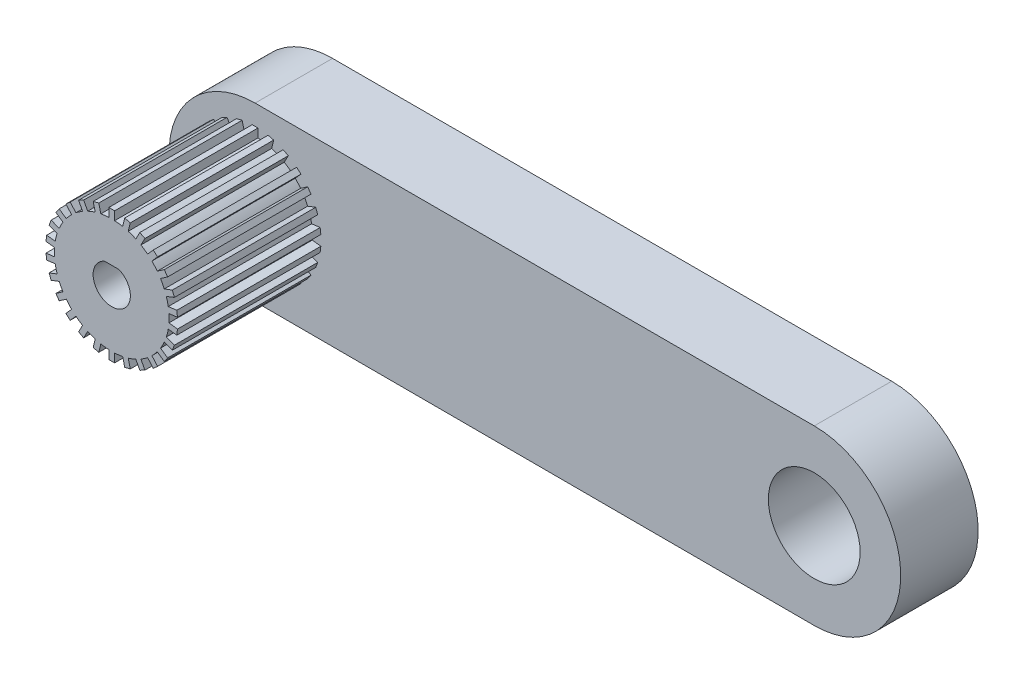
SolidWorks part; units mm, degrees
ref_plane "Front Plane" through (0, 0, 0) normal (0, 0, 1) x (1, 0, 0)
ref_plane "Top Plane" through (0, 0, 0) normal (0, 1, 0) x (1, 0, 0)
ref_plane "Right Plane" through (0, 0, 0) normal (1, 0, 0) x (0, 0, -1)
sketch "Sketch1" plane through (0, 0, 0) normal (0, 0, 1) x (1, 0, 0)
  line L1 (0, 15) -> (97.5002, 15)
  line L2 (0, -15) -> (97.4767, -15.1517)
  line L4 (32.5002, 7.4241) -> (97.5002, 7.4241)
  line L5 (32.5002, -7.5759) -> (97.5002, -7.5759)
  line L6 (32.5002, 7.4241) -> (32.5002, -7.5759)
  arc A0 (0, 15) -> (0, -15) centre (0, 0) ccw
  arc A1 (97.5002, -7.5759) -> (97.5002, 7.4241) centre (97.5002, -0.0759) ccw
  arc A2 (32.5002, 7.4241) -> (32.5002, -7.5759) centre (32.5002, -0.0759) ccw
  arc A3 (97.4767, -15.1517) -> (97.5002, 15) centre (97.5002, -0.0759) ccw
  dimension "D1" = 30
  dimension "D3" = 15
  dimension "D5" = 15
  dimension "D4" = 65
extrude "Boss-Extrude1" add sketch "Sketch1" along normal blind 15 contours L2 A3 L1 A0 A2 L4 A1 L5
sketch "Sketch2" plane through (0, 0, 15) normal (0, 0, 1) x (1, 0, 0)
  circle A0 centre (0, 0) radius 2.575
  circle A1 centre (0, 0) radius 10
  dimension "D1" = 5.15
  dimension "D2" = 20
extrude "Boss-Extrude2" add sketch "Sketch2" along normal blind 20
sketch "Sketch4" plane through (0, 0, 0) normal (0, 0, -1) x (-1, 0, 0)
  line L1 (120.8394, 33.9708) -> (-120.8394, 33.9708)
  line L2 (120.8394, 33.9708) -> (120.8394, -33.9708)
  line L3 (120.8394, -33.9708) -> (-120.8394, -33.9708)
  line L4 (-120.8394, 33.9708) -> (-120.8394, -33.9708)
  line L5 (120.8394, 33.9708) -> (-120.8394, -33.9708) construction
  line L6 (120.8394, -33.9708) -> (-120.8394, 33.9708) construction
  point P0 (0, 0)
extrude "Cut-Extrude2" cut sketch "Sketch4" against normal blind 1.5
sketch "Sketch5" plane through (0, 0, 35) normal (0, 0, 1) x (1, 0, 0)
  circle A0 centre (0, 0) radius 2.575
  circle A1 centre (0, 0) radius 10
extrude "Boss-Extrude3" add sketch "Sketch5" along normal blind 10
sketch "Sketch6" plane through (0, 0, 1.5) normal (0, 0, -1) x (-1, 0, 0)
  circle A0 centre (-97.5002, -0.0759) radius 8
  dimension "D1" = 16
extrude "Cut-Extrude3" cut sketch "Sketch6" against normal through all
sketch "Sketch7" plane through (0, 0, 1.5) normal (0, 0, -1) x (-1, 0, 0)
  line L0 (-94.7163, 7.4241) -> (-32.5002, 7.4241)
  line L1 (-94.7163, -7.5759) -> (-32.5002, -7.5759)
  circle A0 centre (-97.5002, -0.0759) radius 8
  circle A1 centre (-32.5002, -0.0759) radius 7.5
  line M1 (-32.5002, -7.5759) -> (-94.7163, -7.5759)
  line M3 (-94.7163, 7.4241) -> (-32.5002, 7.4241)
  arc M4 (-32.5002, 7.4241) -> (-32.5002, -7.5759) centre (-32.5002, -0.0759) cw
extrude "Boss-Extrude4" add sketch "Sketch7" against normal up to surface (13.5 mm away) contours A1 A0 M3 M1 | A1 M4 up to face at (64.4292, -0.0759, 15)
sketch "Sketch9" plane through (0, 0, 45) normal (0, 0, 1) x (1, 0, 0)
  line L0 (-1.25, 3) -> (1.25, 3)
  arc A0 (-1.25, 3) -> (1.25, 3) centre (0, 0) ccw
  dimension "D1" = 6.5
extrude "Cut-Extrude4" cut sketch "Sketch9" against normal through all both and the other way through all
sketch "Sketch10" plane through (0, 0, 45) normal (0, 0, 1) x (1, 0, 0)
  circle A0 centre (0, 0) radius 10
sketch "Sketch11" plane through (0, 0, 45) normal (0, 0, 1) x (1, 0, 0)
  circle A0 centre (0, 0) radius 10
extrude "Cut-Extrude5" cut sketch "Sketch11" against normal blind 5
sketch "Sketch12" plane through (0, 0, 40) normal (0, 0, 1) x (1, 0, 0)
  line L0 (0, 22.5639) -> (0, -24.3279) construction
  line L1 (-0.5021, 11.4874) -> (0.5021, 11.4874)
  line L2 (-0.5021, 11.4874) -> (-0.5021, 9.9874)
  line L3 (0.5021, 11.4874) -> (0.5021, 9.9874)
  line L4 (2.2616, 11.2737) -> (1.9027, 9.8173)
  line L5 (2.2616, 11.2737) -> (3.2366, 11.0334)
  line L6 (3.2366, 11.0334) -> (2.8776, 9.577)
  line L7 (4.8939, 10.4049) -> (4.1968, 9.0767)
  line L8 (4.8939, 10.4049) -> (5.783, 9.9383)
  line L9 (5.783, 9.9383) -> (5.0859, 8.6101)
  line L10 (7.2418, 8.9314) -> (6.2471, 7.8086)
  line L11 (7.2418, 8.9314) -> (7.9933, 8.2655)
  line L12 (7.9933, 8.2655) -> (6.9987, 7.1427)
  line L13 (9.1687, 6.9388) -> (7.9343, 6.0867)
  line L14 (9.1687, 6.9388) -> (9.7391, 6.1124)
  line L15 (9.7391, 6.1124) -> (8.5047, 5.2603)
  line L16 (10.5629, 4.5429) -> (9.1603, 4.011)
  line L17 (10.5629, 4.5429) -> (10.9189, 3.6041)
  line L18 (10.9189, 3.6041) -> (9.5164, 3.0721)
  line L19 (11.3431, 1.883) -> (9.8541, 1.7022)
  line L20 (11.3431, 1.883) -> (11.4641, 0.8863)
  line L21 (11.4641, 0.8863) -> (9.9751, 0.7054)
  line L22 (11.4641, -0.8863) -> (9.9751, -0.7054)
  line L23 (11.4641, -0.8863) -> (11.3431, -1.883)
  line L24 (11.3431, -1.883) -> (9.8541, -1.7022)
  line L25 (10.9189, -3.6041) -> (9.5164, -3.0721)
  line L26 (10.9189, -3.6041) -> (10.5629, -4.5429)
  line L27 (10.5629, -4.5429) -> (9.1603, -4.011)
  line L28 (9.7391, -6.1124) -> (8.5047, -5.2603)
  line L29 (9.7391, -6.1124) -> (9.1687, -6.9388)
  line L30 (9.1687, -6.9388) -> (7.9343, -6.0867)
  line L31 (7.9933, -8.2655) -> (6.9987, -7.1427)
  line L32 (7.9933, -8.2655) -> (7.2418, -8.9314)
  line L33 (7.2418, -8.9314) -> (6.2471, -7.8086)
  line L34 (5.783, -9.9383) -> (5.0859, -8.6101)
  line L35 (5.783, -9.9383) -> (4.8939, -10.4049)
  line L36 (4.8939, -10.4049) -> (4.1968, -9.0767)
  line L37 (3.2366, -11.0334) -> (2.8776, -9.577)
  line L38 (3.2366, -11.0334) -> (2.2616, -11.2737)
  line L39 (2.2616, -11.2737) -> (1.9027, -9.8173)
  line L40 (0.5021, -11.4874) -> (0.5021, -9.9874)
  line L41 (0.5021, -11.4874) -> (-0.5021, -11.4874)
  line L42 (-0.5021, -11.4874) -> (-0.5021, -9.9874)
  line L43 (-2.2616, -11.2737) -> (-1.9027, -9.8173)
  line L44 (-2.2616, -11.2737) -> (-3.2366, -11.0334)
  line L45 (-3.2366, -11.0334) -> (-2.8776, -9.577)
  line L46 (-4.8939, -10.4049) -> (-4.1968, -9.0767)
  line L47 (-4.8939, -10.4049) -> (-5.783, -9.9383)
  line L48 (-5.783, -9.9383) -> (-5.0859, -8.6101)
  line L49 (-7.2418, -8.9314) -> (-6.2471, -7.8086)
  line L50 (-7.2418, -8.9314) -> (-7.9933, -8.2655)
  line L51 (-7.9933, -8.2655) -> (-6.9987, -7.1427)
  line L52 (-9.1687, -6.9388) -> (-7.9343, -6.0867)
  line L53 (-9.1687, -6.9388) -> (-9.7391, -6.1124)
  line L54 (-9.7391, -6.1124) -> (-8.5047, -5.2603)
  line L55 (-10.5629, -4.5429) -> (-9.1603, -4.011)
  line L56 (-10.5629, -4.5429) -> (-10.9189, -3.6041)
  line L57 (-10.9189, -3.6041) -> (-9.5164, -3.0721)
  line L58 (-11.3431, -1.883) -> (-9.8541, -1.7022)
  line L59 (-11.3431, -1.883) -> (-11.4641, -0.8863)
  line L60 (-11.4641, -0.8863) -> (-9.9751, -0.7054)
  line L61 (-11.4641, 0.8863) -> (-9.9751, 0.7054)
  line L62 (-11.4641, 0.8863) -> (-11.3431, 1.883)
  line L63 (-11.3431, 1.883) -> (-9.8541, 1.7022)
  line L64 (-10.9189, 3.6041) -> (-9.5164, 3.0721)
  line L65 (-10.9189, 3.6041) -> (-10.5629, 4.5429)
  line L66 (-10.5629, 4.5429) -> (-9.1603, 4.011)
  line L67 (-9.7391, 6.1124) -> (-8.5047, 5.2603)
  line L68 (-9.7391, 6.1124) -> (-9.1687, 6.9388)
  line L69 (-9.1687, 6.9388) -> (-7.9343, 6.0867)
  line L70 (-7.9933, 8.2655) -> (-6.9987, 7.1427)
  line L71 (-7.9933, 8.2655) -> (-7.2418, 8.9314)
  line L72 (-7.2418, 8.9314) -> (-6.2471, 7.8086)
  line L73 (-5.783, 9.9383) -> (-5.0859, 8.6101)
  line L74 (-5.783, 9.9383) -> (-4.8939, 10.4049)
  line L75 (-4.8939, 10.4049) -> (-4.1968, 9.0767)
  line L76 (-3.2366, 11.0334) -> (-2.8776, 9.577)
  line L77 (-3.2366, 11.0334) -> (-2.2616, 11.2737)
  line L78 (-2.2616, 11.2737) -> (-1.9027, 9.8173)
  circle A0 centre (0, 0) radius 10
  point P9 (0, 11.4874)
  point P112 (0, 0)
  circle M5 centre (0, 0) radius 10
  dimension "D1" = 1.5
  dimension "D2" = 0.5021
  dimension "D3" = 26
extrude "Boss-Extrude5" add sketch "Sketch12" against normal up to surface (25 mm away) contours L72 L71 L70 M5 | L69 L68 L67 M5 | L66 L65 L64 M5 | L63 L62 L61 M5 | L60 L59 L58 M5 | L57 L56 L55 M5 | L54 L53 L52 M5 | L51 L50 L49 M5 | L48 L47 L46 M5 | L45 L44 L43 M5 | A0 L0 L41 L40 | L0 L42 L41 M5 | L39 L38 L37 M5 | L36 L35 L34 M5 | L33 L32 L31 M5 | L30 L29 L28 M5 | L27 L26 L25 M5 | L24 L23 L22 M5 | L21 L20 L19 M5 | L18 L17 L16 M5 | L15 L14 L13 M5 | L12 L11 L10 M5 | L9 L8 L7 M5 | L6 L5 L4 M5 | L1 L0 L3 M5 | L0 L1 L2 A0 | L78 L77 L76 M5 | L75 L74 L73 M5 up to face at (105.5002, -0.0759, 15)
